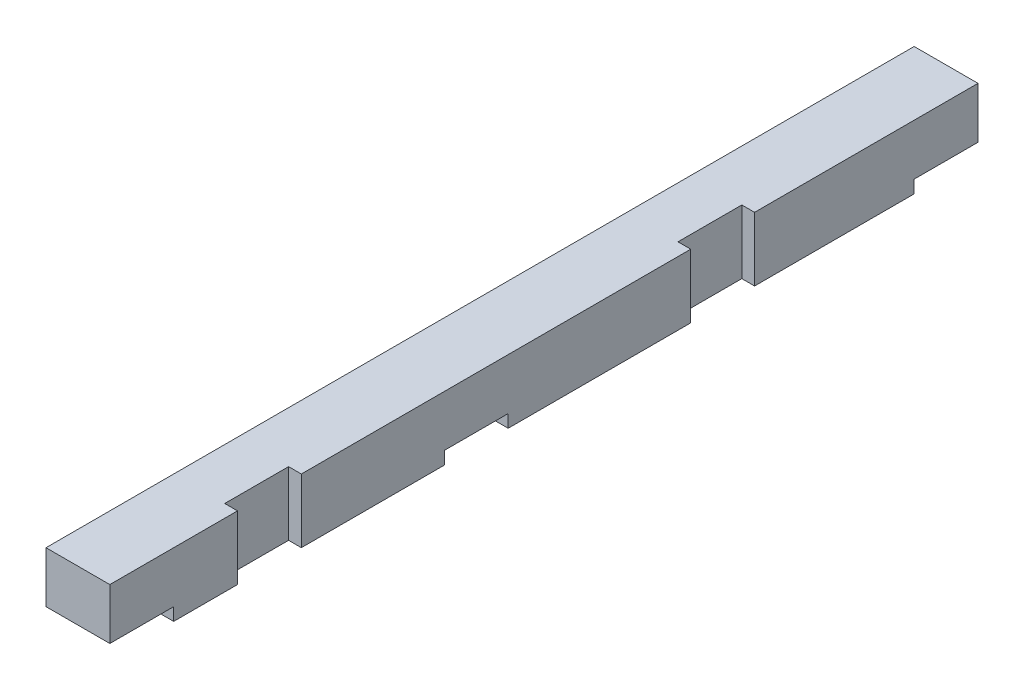
SolidWorks part; units mm, degrees
ref_plane "Plan de face" through (0, 0, 0) normal (0, 0, 1) x (1, 0, 0)
ref_plane "Plan de dessus" through (0, 0, 0) normal (0, 1, 0) x (1, 0, 0)
ref_plane "Plan de droite" through (0, 0, 0) normal (1, 0, 0) x (0, 0, -1)
sketch "Esquisse1" plane through (0, 0, 0) normal (0, 0, 1) x (1, 0, 0)
  line L1 (0, 0) -> (10, 0)
  line L2 (0, 0) -> (0, 10)
  line L3 (0, 10) -> (10, 10)
  line L4 (10, 0) -> (10, 10)
  dimension "D1" = 10
  dimension "D2" = 10
extrude "Boss.-Extru.1" add sketch "Esquisse1" along normal blind 136
sketch "Esquisse2" plane through (10, 0, 0) normal (1, 0, 0) x (0, 0, -1)
  line L0 (-136, 0) -> (-136, 10) construction
  line L1 (-136, 2) -> (-126, 2)
  line L2 (-136, 2) -> (-136, 0)
  line L3 (-136, 0) -> (-126, 0)
  line L4 (-126, 2) -> (-126, 0)
  line L5 (-136, 0) -> (0, 0) construction
  line L6 (-136, 0) -> (0, 0) construction
  line L7 (-83.6, 2) -> (-73.6, 2)
  line L8 (-83.6, 2) -> (-83.6, 0)
  line L9 (-83.6, 0) -> (-73.6, 0)
  line L10 (-73.6, 2) -> (-73.6, 0)
  line L12 (-10, 2) -> (0, 2)
  line L13 (-10, 2) -> (-10, 0)
  line L14 (-10, 0) -> (0, 0)
  line L15 (0, 2) -> (0, 0)
  dimension "D1" = 10
  dimension "D2" = 2
  dimension "D3" = 10
  dimension "D4" = 2
  dimension "D5" = 42.4
  dimension "D6" = 10
  dimension "D7" = 2
extrude "Enlèv. mat.-Extru.1" cut sketch "Esquisse2" against normal through all
sketch "Esquisse3" plane through (10, 0, 0) normal (1, 0, 0) x (0, 0, -1)
  line L0 (-73.6, 0) -> (-10, 0) construction
  line L1 (-45, 0) -> (-35, 0)
  line L2 (-45, 0) -> (-45, 10)
  line L3 (-45, 10) -> (-35, 10)
  line L4 (-35, 0) -> (-35, 10)
  line L5 (-136, 10) -> (0, 10) construction
  line L6 (0, 2) -> (0, 10) construction
  point P10 (0, 6)
  dimension "D1" = 10
  dimension "D2" = 35
extrude "Enlèv. mat.-Extru.2" cut sketch "Esquisse3" against normal blind 2
sketch "Esquisse4" plane through (10, 0, 0) normal (1, 0, 0) x (0, 0, -1)
  line L0 (-136, 10) -> (-45, 10) construction
  line L1 (-116, 10) -> (-106, 10)
  line L2 (-116, 10) -> (-116, 0)
  line L3 (-116, 0) -> (-106, 0)
  line L4 (-106, 10) -> (-106, 0)
  line L5 (-126, 0) -> (-83.6, 0) construction
  line L6 (-136, 2) -> (-136, 10) construction
  dimension "D1" = 10
  dimension "D2" = 20
extrude "Enlèv. mat.-Extru.3" cut sketch "Esquisse4" against normal blind 2
